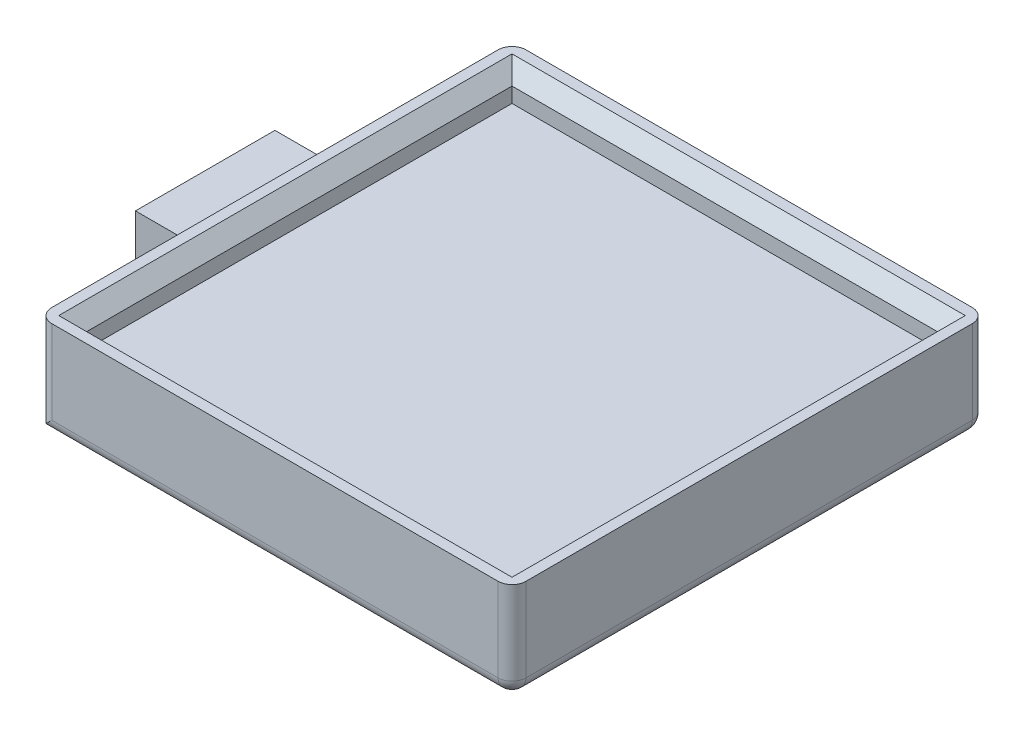
SolidWorks part; units mm, degrees
ref_plane "前视基准面" through (0, 0, 0) normal (0, 0, 1) x (1, 0, 0)
ref_plane "上视基准面" through (0, 0, 0) normal (0, 1, 0) x (1, 0, 0)
ref_plane "右视基准面" through (0, 0, 0) normal (1, 0, 0) x (0, 0, -1)
other "Configuration Table"
sketch "草图1" plane through (0, 0, 0) normal (0, 1, 0) x (1, 0, 0)
  line L0 (0, 10) -> (5, 10)
  line L1 (5, 10) -> (5, 22)
  line L2 (5, 22) -> (39, 22)
  line L3 (39, 22) -> (39, -12)
  line L4 (39, -12) -> (5, -12)
  line L5 (5, -12) -> (5, 0)
  line L6 (5, 0) -> (0, 0)
  line L7 (0, 0) -> (0, 10)
  dimension "D1" = 5
  dimension "D2" = 10
  dimension "D3" = 5
  dimension "D4" = 34
  dimension "D5" = 34
extrude "凸台-拉伸1" add sketch "草图1" along normal blind 5 contours L7 L0 L1 L2 L3 L4 L5 L6
ref_plane "基准面1" through (0, 5, 0) normal (0, 1, 0) x (1, 0, 0)
sketch "草图2" plane through (0, 5, 0) normal (0, 1, 0) x (1, 0, 0)
  line L0 (5, 10) -> (5, 22) construction
  line L1 (7, 20) -> (37.1, 20)
  line L2 (7, 20) -> (7, -10.1)
  line L3 (7, -10.1) -> (37.1, -10.1)
  line L4 (37.1, 20) -> (37.1, -10.1)
  line L6 (5, 22) -> (39, 22)
  line L7 (5, 22) -> (5, -12)
  line L8 (0, 0) -> (5, 0)
  line L9 (0, 10) -> (0, 0)
  line L10 (5, 10) -> (0, 10)
  line L11 (5, 22) -> (5, 10)
  line L12 (39, 22) -> (5, 22)
  line L13 (39, -12) -> (39, 22)
  line L14 (5, -12) -> (39, -12)
  line L15 (5, 0) -> (5, -12)
  line L16 (0, 0) -> (5, 0)
  line L17 (0, 10) -> (0, 0)
  line L18 (5, 10) -> (0, 10)
  line L19 (5, 22) -> (5, 10)
  line L20 (39, 22) -> (5, 22)
  line L21 (39, -12) -> (39, 22)
  line L22 (5, -12) -> (39, -12)
  line L23 (5, 0) -> (5, -12)
  line L24 (5, -12) -> (39, -12)
  line L25 (39, 22) -> (39, -12)
  dimension "D2" = 2
  dimension "D3" = 2
  dimension "D4" = 30.1
  dimension "D1" = 0
extrude "凸台-拉伸2" add sketch "草图2" along normal blind 2 contours L7 L22 L21 L6 L1 L4 L3 L2
ref_plane "基准面2" through (0, 7, 0) normal (0, 1, 0) x (1, 0, 0)
sketch "草图3" plane through (0, 7, 0) normal (0, 1, 0) x (1, 0, 0)
  line L1 (6.75, 20.25) -> (37.25, 20.25)
  line L2 (6.75, 20.25) -> (6.75, -10.25)
  line L3 (6.75, -10.25) -> (37.25, -10.25)
  line L4 (5, 22) -> (5, -12)
  line L5 (5, -12) -> (39, -12)
  line L6 (39, -12) -> (39, 22)
  line L7 (39, 22) -> (5, 22)
  line L8 (5, 22) -> (5, -12)
  line L9 (5, -12) -> (39, -12)
  line L10 (39, -12) -> (39, 22)
  line L11 (39, 22) -> (5, 22)
  line L12 (37.25, 20.25) -> (37.25, -10.25)
  dimension "D2" = 30.5
  dimension "D3" = 30.5
  dimension "D4" = 1.75
  dimension "D5" = 1.75
  dimension "D1" = 0
extrude "切除-拉伸2" cut sketch "草图3" against normal blind 2.08 contours L2 L1 L12 L3
chamfer "倒角1" distance 1 angle 45 4 edges at (22, 7, -20.25) (37.25, 7, -5) (22, 7, 10.25) (6.75, 7, -5)
fillet "圆角2" radius 1 7 edges at (22, 0, 12) (22, 0, -22) (39, 0, -5) (39, 3.5, 12) (5, 3.5, -22) (39, 3.5, -22) (5, 3.5, 12)
